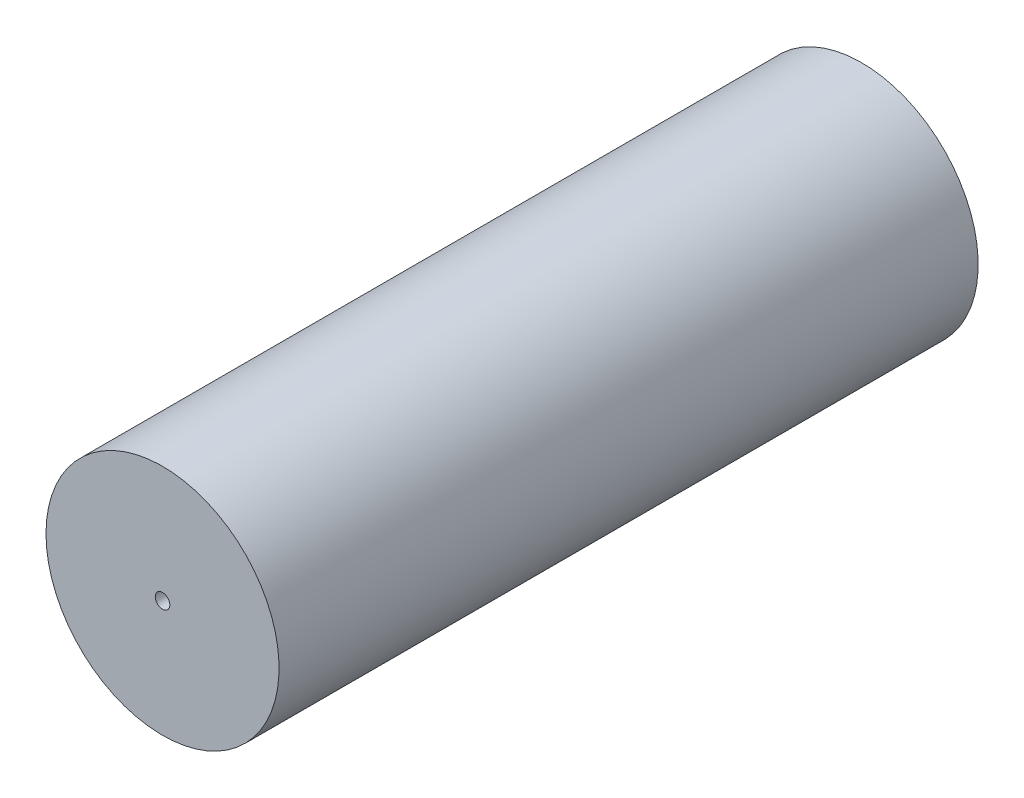
SolidWorks part; units mm, degrees
ref_plane "Front Plane" through (0, 0, 0) normal (0, 0, 1) x (1, 0, 0)
ref_plane "Top Plane" through (0, 0, 0) normal (0, 1, 0) x (1, 0, 0)
ref_plane "Right Plane" through (0, 0, 0) normal (1, 0, 0) x (0, 0, -1)
sketch "Sketch1" plane through (0, 0, 0) normal (0, 0, 1) x (1, 0, 0)
  circle A0 centre (0, 0) radius 12.7
  dimension "D1" = 25.4
extrude "Boss-Extrude1" add sketch "Sketch1" along normal blind 76.2
sketch "Sketch2" plane through (0, 0, 76.2) normal (0, 0, 1) x (1, 0, 0)
  circle A0 centre (0, 0) radius 0.7937
  dimension "D1" = 1.5875
extrude "Cut-Extrude1" cut sketch "Sketch2" against normal through all
